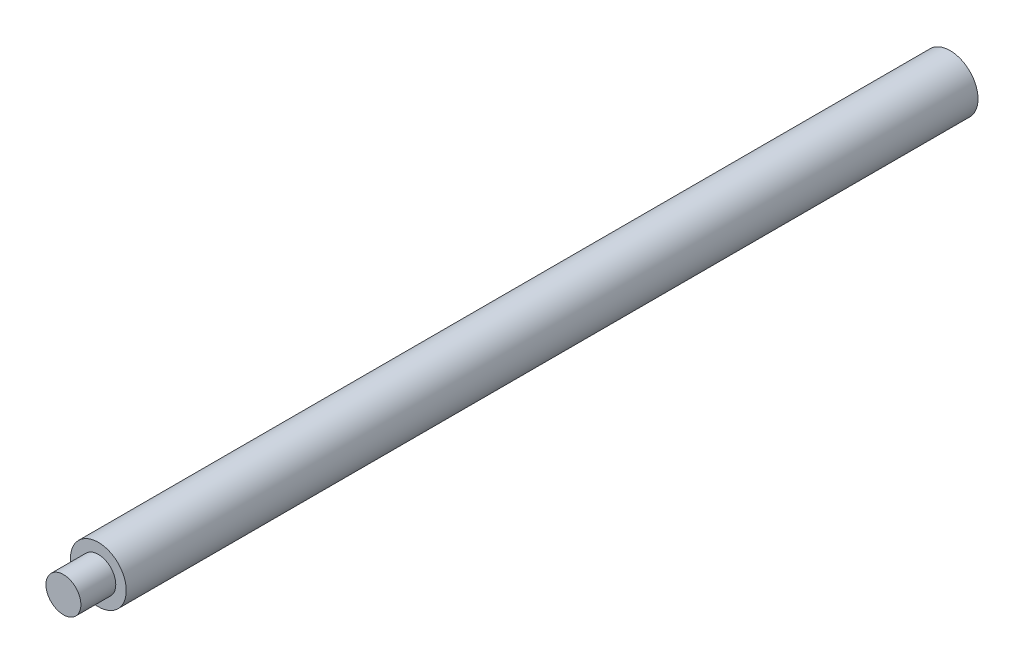
SolidWorks part; units mm, degrees
ref_plane "前基準面" through (0, 0, 0) normal (0, 0, 1) x (1, 0, 0)
ref_plane "上基準面" through (0, 0, 0) normal (0, 1, 0) x (1, 0, 0)
ref_plane "右基準面" through (0, 0, 0) normal (1, 0, 0) x (0, 0, -1)
sketch "草圖2" plane through (0, 0, 0) normal (0, 0, 1) x (1, 0, 0)
  circle A0 centre (0, 0) radius 4
  dimension "D1" = 8
extrude "填料-伸長1" add sketch "草圖2" along normal blind 127
sketch "草圖3" plane through (0, 0, 127) normal (0, 0, 1) x (1, 0, 0)
  circle A0 centre (0, 0) radius 4
  circle A1 centre (0, 0) radius 2.5
  dimension "D1" = 5
extrude "除料-伸長1" cut sketch "草圖3" against normal blind 5
